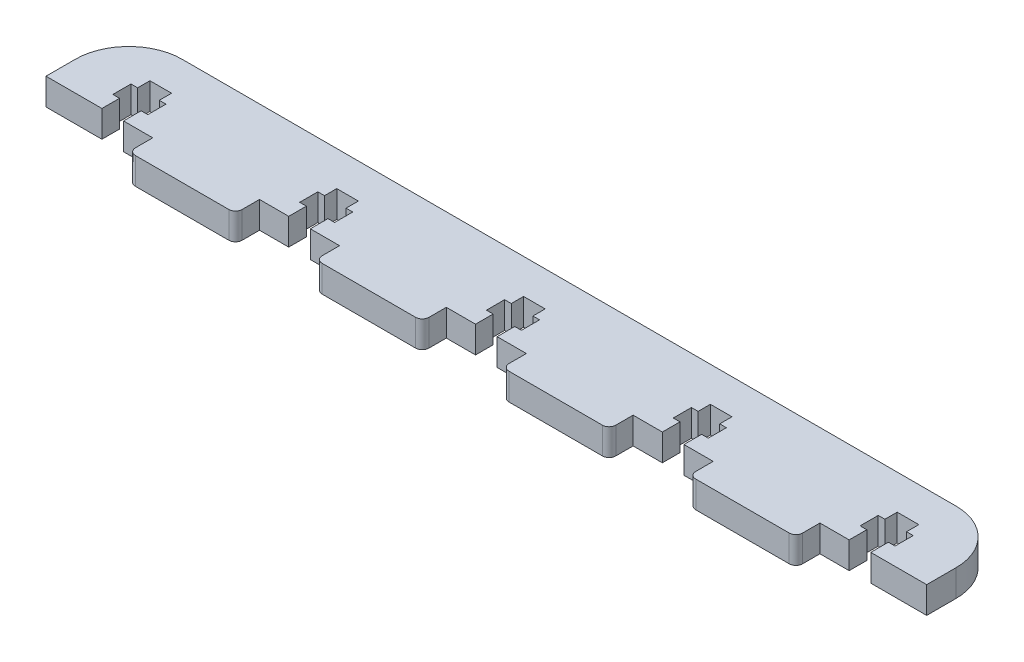
SolidWorks part; units mm, degrees
ref_plane "Front Plane" through (0, 0, 0) normal (0, 0, 1) x (1, 0, 0)
ref_plane "Top Plane" through (0, 0, 0) normal (0, 1, 0) x (1, 0, 0)
ref_plane "Right Plane" through (0, 0, 0) normal (1, 0, 0) x (0, 0, -1)
sketch "Sketch1" plane through (0, 0, 0) normal (0, 1, 0) x (1, 0, 0)
  line L1 (-165, 20) -> (165, 20)
  line L2 (-165, 20) -> (-165, -20)
  line L3 (-165, -20) -> (165, -20)
  line L4 (165, 20) -> (165, -20)
  line L5 (-165, 20) -> (165, -20) construction
  line L6 (-165, -20) -> (165, 20) construction
  point P0 (0, 0)
  dimension "D1" = 40
  dimension "D2" = 330
extrude "Boss-Extrude1" add sketch "Sketch1" along normal blind 10 contours L1 L4 L3 L2
sketch "Sketch2" plane through (0, 10, 0) normal (0, 1, 0) x (1, 0, 0)
  line L0 (0, -6.9) -> (0, -20) construction
  line L1 (-165, -20) -> (165, -20) construction
  line L3 (-4.05, 7) -> (4.05, 7)
  line L4 (-4.05, 7) -> (-4.05, -20)
  line L5 (-4.05, -20) -> (4.05, -20)
  line L6 (4.05, 7) -> (4.05, -20)
  line L7 (-4.05, 7) -> (4.05, -20) construction
  line L8 (-4.05, -20) -> (4.05, 7) construction
  line L9 (-6.55, 2.4) -> (6.55, 2.4)
  line L10 (-6.55, 2.4) -> (-6.55, -4.4)
  line L11 (-6.55, -4.4) -> (6.55, -4.4)
  line L12 (6.55, 2.4) -> (6.55, -4.4)
  line L13 (-6.55, 2.4) -> (6.55, -4.4) construction
  line L14 (-6.55, -4.4) -> (6.55, 2.4) construction
  line L15 (-15, -11) -> (15, -11)
  line L16 (-15, -11) -> (-15, -20)
  line L17 (-15, -20) -> (15, -20)
  line L18 (15, -11) -> (15, -20)
  line L19 (-15, -11) -> (15, -20) construction
  line L20 (-15, -20) -> (15, -11) construction
  point P4 (0, -6.5)
  point P9 (0, -1)
  point P14 (0, -15.5)
  line M12 (-165, -20) -> (165, -20)
  dimension "D1" = 27
  dimension "D2" = 8.1
  dimension "D3" = 6.8
  dimension "D4" = 13.1
  dimension "D5" = 19
  dimension "D6" = 30
  dimension "D7" = 9
extrude "Cut-Extrude1" cut sketch "Sketch2" against normal through all contours L18 L15 L6 M12 | L15 L4 L6 M12 | L15 L16 L4 M12 | L4 L15 L6 L11 | L4 L11 L6 L9 | L10 L11 L4 L9 | L4 L9 L6 L3 | L12 L9 L6 L11
fillet "Fillet1" radius 2.5 2 edges at (15, 5, 20) (-15, 5, 20)
pattern_linear "LPattern1" count 3 spacing 70 along (1, 0, 0) count 3 spacing 70 along (-1, 0, 0) of "Cut-Extrude1", "Fillet1"
sketch "Sketch3" plane through (0, 10, 0) normal (0, 1, 0) x (1, 0, 0)
  line L1 (-155, -11) -> (-165, -11)
  line L2 (-155, -11) -> (-155, -20)
  line L3 (-155, -20) -> (-165, -20)
  line L4 (-165, -11) -> (-165, -20)
extrude "Cut-Extrude2" cut sketch "Sketch3" against normal through all
mirror "Mirror1" about plane through (0, 0, 0) normal (1, 0, 0) of "Cut-Extrude2"
fillet "Fillet2" radius 20 2 edges at (165, 5, -20) (-165, 5, -20)
